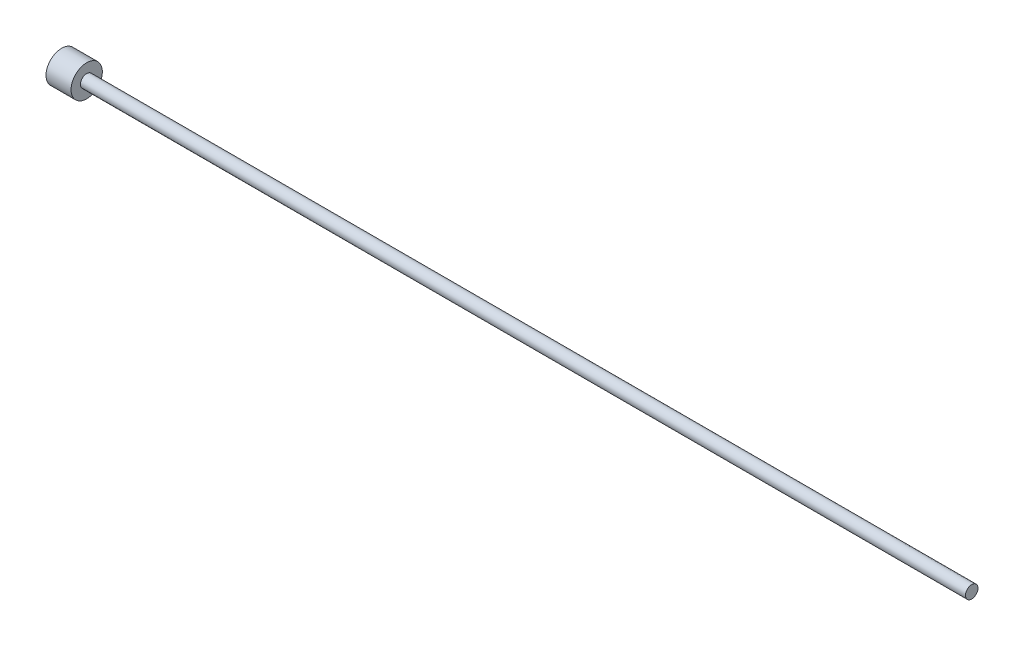
SolidWorks part; units mm, degrees
ref_plane "前视基准面" through (0, 0, 0) normal (0, 0, 1) x (1, 0, 0)
ref_plane "上视基准面" through (0, 0, 0) normal (0, 1, 0) x (1, 0, 0)
ref_plane "右视基准面" through (0, 0, 0) normal (1, 0, 0) x (0, 0, -1)
sketch "草图1" plane through (0, 0, 0) normal (0, 1, 0) x (1, 0, 0)
  line L0 (0, 0) -> (727, 0) construction
  line L1 (0, 0) -> (0, 12.5)
  line L2 (0, 12.5) -> (20, 12.5)
  line L3 (20, 12.5) -> (20, 5)
  line L4 (20, 5) -> (727, 5)
  line L5 (727, 5) -> (727, 0)
  line L6 (0, 0) -> (727, 0)
  dimension "D1" = 12.5
  dimension "D2" = 20
  dimension "D3" = 5
  dimension "D4" = 727
revolve "旋转1" add sketch "草图1" angle 360 about L0
